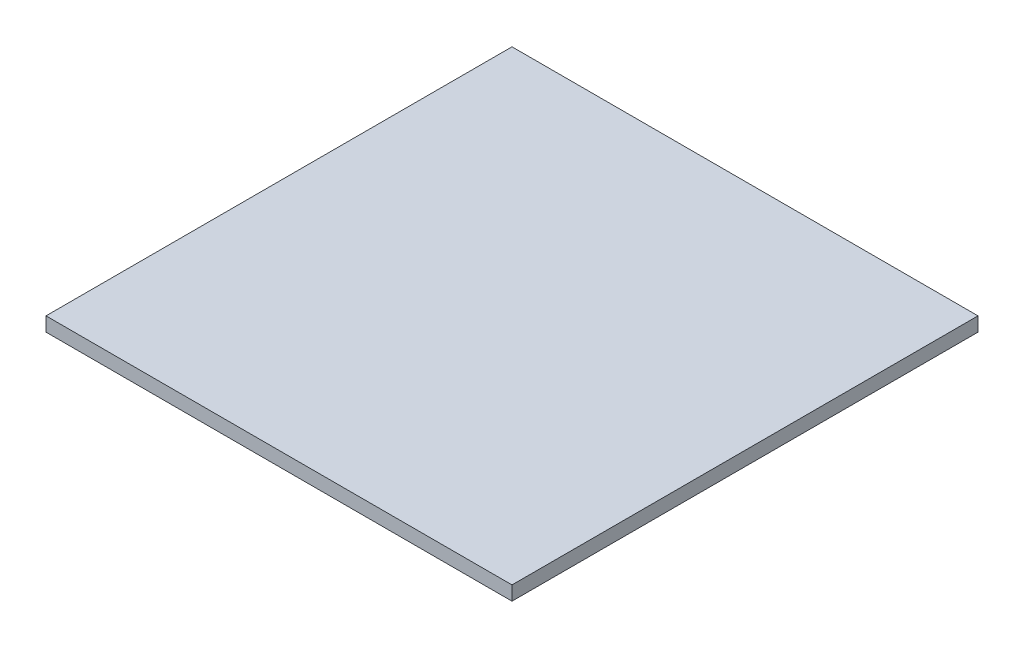
SolidWorks part; units mm, degrees
ref_plane "Front Plane" through (0, 0, 0) normal (0, 0, 1) x (1, 0, 0)
ref_plane "Top Plane" through (0, 0, 0) normal (0, 1, 0) x (1, 0, 0)
ref_plane "Right Plane" through (0, 0, 0) normal (1, 0, 0) x (0, 0, -1)
sketch "Sketch1" plane through (0, 0, 0) normal (0, 1, 0) x (1, 0, 0)
  line L1 (-165, -165) -> (165, -165)
  line L2 (-165, -165) -> (-165, 165)
  line L3 (-165, 165) -> (165, 165)
  line L4 (165, -165) -> (165, 165)
  line L5 (-165, -165) -> (165, 165) construction
  line L6 (-165, 165) -> (165, -165) construction
  point P0 (0, 0)
  dimension "D1" = 330
extrude "Boss-Extrude1" add sketch "Sketch1" along normal blind 10
